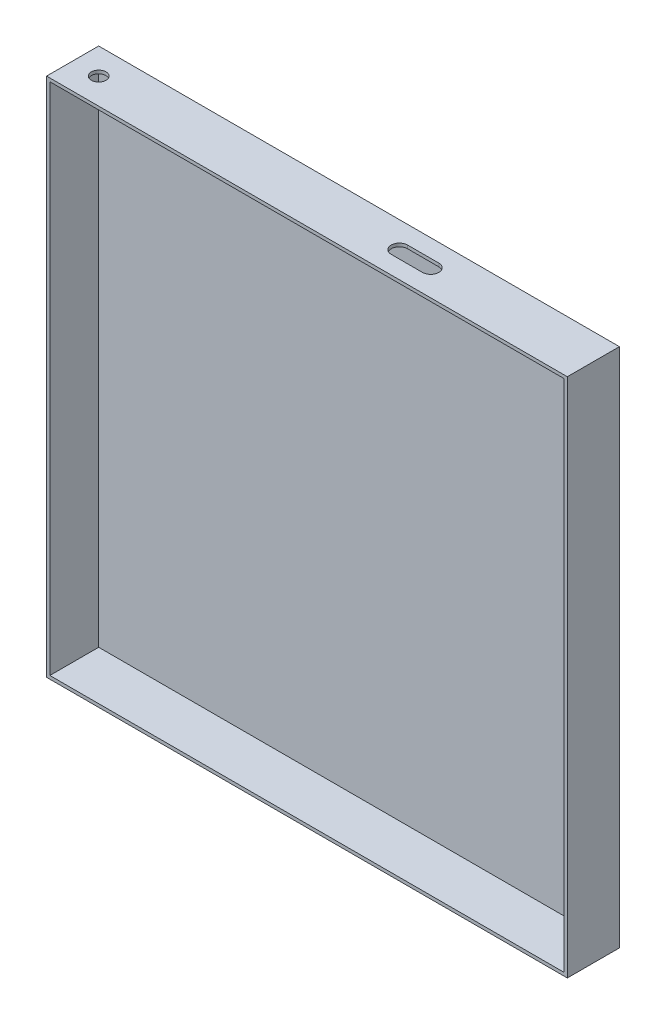
SolidWorks part; units mm, degrees
ref_plane "Front Plane" through (0, 0, 0) normal (0, 0, 1) x (1, 0, 0)
ref_plane "Top Plane" through (0, 0, 0) normal (0, 1, 0) x (1, 0, 0)
ref_plane "Right Plane" through (0, 0, 0) normal (1, 0, 0) x (0, 0, -1)
sketch "Sketch1" plane through (0, 0, 0) normal (0, 0, 1) x (1, 0, 0)
  line L1 (0, 0) -> (508, 0)
  line L2 (0, 0) -> (0, 508)
  line L3 (0, 508) -> (508, 508)
  line L4 (508, 0) -> (508, 508)
  dimension "D1" = 508
  dimension "D2" = 508
extrude "Boss-Extrude1" add sketch "Sketch1" along normal blind 50.8
shell "Shell1" thickness 3.175
sketch "Sketch2" plane through (0, 508, 0) normal (0, 1, 0) x (1, 0, 0)
  line L0 (349.25, -25.4) -> (318.77, -25.4) construction
  line L1 (349.25, -33.3375) -> (318.77, -33.3375)
  line L2 (349.25, -17.4625) -> (318.77, -17.4625)
  line L3 (0, -25.4) -> (25.4, -25.4) construction
  line L4 (0, -50.8) -> (0, 0) construction
  circle A0 centre (25.4, -25.4) radius 7.1437
  arc A1 (349.25, -33.3375) -> (349.25, -17.4625) centre (349.25, -25.4) ccw
  arc A2 (318.77, -17.4625) -> (318.77, -33.3375) centre (318.77, -25.4) ccw
  point P7 (334.01, -25.4)
  dimension "D1" = 14.2875
  dimension "D4" = 15.875
  dimension "D2" = 293.37
  dimension "D3" = 25.4
  dimension "D5" = 30.48
extrude "Cut-Extrude1" cut sketch "Sketch2" against normal blind 417.576
ref_plane "Plane1" through (349.25, 508, 17.4625) normal (-1, 0, 0) x (0, 0, 1)
